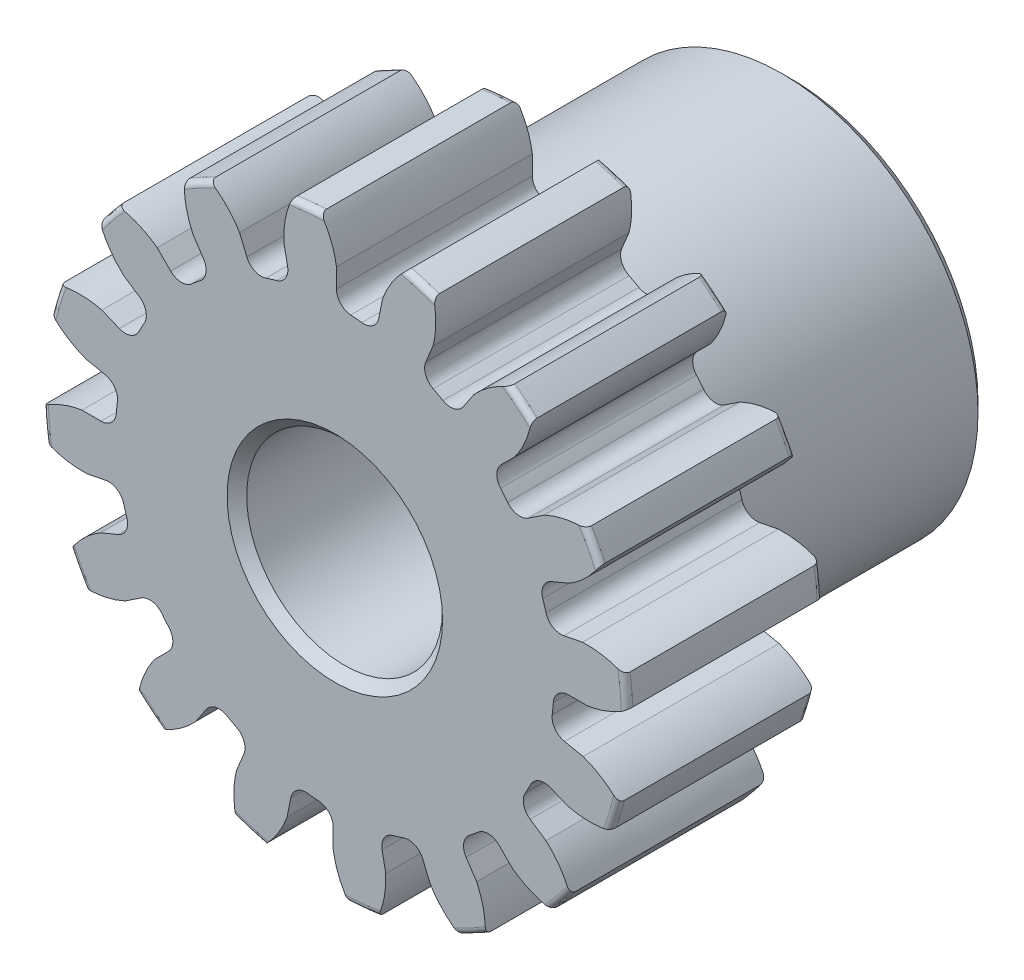
SolidWorks part; units mm, degrees
ref_plane "Front" through (0, 0, 0) normal (0, 0, 1) x (1, 0, 0)
ref_plane "Top" through (0, 0, 0) normal (0, 1, 0) x (1, 0, 0)
ref_plane "Right" through (0, 0, 0) normal (1, 0, 0) x (0, 0, -1)
sketch "Sketch1" plane through (0, 0, 0) normal (0, 0, 1) x (1, 0, 0)
  line L0 (-203.2, 0) -> (203.2, 0) construction
  circle A0 centre (0, 0) radius 7.112
  circle A1 centre (0, 0) radius 6.35 construction
  circle A3 centre (0, 0) radius 5.3261 construction
  dimension "D1" = 1.7859
  dimension "OD" = 14.224
  dimension "Ptich Dia" = 12.7
  dimension "Root Dia" = 10.6521
  dimension "D3" = 0.762
  dimension "Number of Teeth" = 406.4
extrude "Boss-Extrude1" add sketch "Sketch1" against normal blind 4.7625
sketch "Sketch2" plane through (0, 0, 0) normal (1, 0, 0) x (0, 0, -1)
  line L0 (4.7625, 0) -> (11.1125, 0)
  line L1 (4.7625, 0) -> (4.7625, 4.7625)
  line L2 (4.7625, 4.7625) -> (11.1125, 4.7625)
  line L3 (11.1125, 4.7625) -> (11.1125, 0)
  point P5 (11.1125, -4.7625)
  point P6 (0, -7.112)
  point P7 (4.7625, -7.112)
  point P9 (0, 7.112)
  dimension "Face Wd" = 4.7625
  dimension "B Hub Dia" = 9.525
  dimension "D O'all Lg." = 11.1125
revolve "Revolve1" add sketch "Sketch2" angle 360 mid plane about L0
fillet "Fillet2" radius 0.1422 3 edges at (7.112, 0, -4.7625) (7.112, 0, 0) (4.7625, 0, -4.7625)
sketch "Sketch3" plane through (0, 0, 0) normal (0, 0, 1) x (1, 0, 0)
  line L0 (0, 0) -> (0, 7.112) construction
  line L1 (-1.5393, 5.9519) -> (0, 6.35)
  line L2 (-9.5921, 6.35) -> (9.5921, 6.35) construction
  line L3 (-9.2865, 3.9483) -> (9.2865, 8.7517) construction
  line L4 (-1.5393, 5.9519) -> (0, 0) construction
  line L5 (-3.9262, 4.7307) -> (0, 0) construction
  line L6 (-3.9262, 4.7307) -> (-0.6424, 7.456) construction
  line L7 (-1.0733, 6.0533) -> (0, 0) construction
  line L8 (-1.0733, 6.0533) -> (0.0225, 6.2476) construction
  arc A0 (-1.5393, 5.9519) -> (-3.9262, 4.7307) centre (0, 0) ccw
  circle A1 centre (0, 0) radius 6.35 construction
  circle A2 centre (0, 0) radius 6.1477 construction
  arc A3 (-1.5393, 5.9519) -> (-1.0733, 6.0533) centre (0, 0) cw
  circle A4 centre (0, 0) radius 7.112 construction
  point P6 (0, 6.35)
  dimension "D1" = 1.5899
  dimension "Pressure Angle" = 14.5
  dimension "D2" = 2.7029
  dimension "D3" = 4.2674
  dimension "D4" = 0.477
  dimension "D5" = 1.1129
sketch "Sketch4" plane through (0, 0, 0) normal (0, 0, 1) x (1, 0, 0)
  line L0 (0, 0) -> (0.6194, 6.289) construction
  line L1 (0.0398, 6.1476) -> (0.0398, 5.3259)
  line L2 (0, 6.35) -> (1.2388, 6.228) construction
  line L3 (1.1603, 6.0372) -> (1, 5.2313)
  line L4 (0.0398, 5.3259) -> (0, 0) construction
  line L5 (0, 0) -> (0, 7.112) construction
  line L6 (-3.9262, 4.7307) -> (-0.6424, 7.456) construction
  line L7 (-3.9262, 4.7307) -> (-0.6424, 7.456) construction
  arc A0 (1, 5.2313) -> (0.0398, 5.3259) centre (0, 0) ccw
  arc A1 (0, 6.35) -> (1.2388, 6.228) centre (0, 0) cw construction
  circle A2 centre (0, 0) radius 6.35 construction
  circle A3 centre (0, 0) radius 6.1477 construction
  circle A4 centre (0, 0) radius 5.3261 construction
  arc A5 (2.0846, 7.1874) -> (-0.6424, 7.456) centre (0, 0) ccw
  spline S0 degree 2 poles (-0.6424, 7.456) (-0.0701, 6.8828) (0.0398, 6.1476) knots 0 0 0 1 1 1
  spline S1 degree 2 poles (2.0846, 7.1874) (1.4115, 6.7368) (1.1603, 6.0372) knots 0 0 0 1 1 1
  dimension "D1" = 1.2468
extrude "Cut-Extrude1" cut sketch "Sketch4" against normal through all
fillet "Fillet1" radius 0.374 2 edges at (1, 5.2313, -2.3813) (0.0398, 5.3259, -2.3813)
pattern_circular "CirPattern1" count 16 over 360 about axis through (0, 0, -4.7625) along (0, 0, 1) of "Cut-Extrude1", "Fillet1"
sketch "Sketch5" plane through (0, 0, 0) normal (0, 0, 1) x (1, 0, 0)
  circle A0 centre (0, 0) radius 2.3813
  circle A1 centre (0, 0) radius 1.5875 construction
  dimension "Bore Min" = 4.7625
  dimension "Bore Max" = 3.175
extrude "Cut-Extrude2" cut sketch "Sketch5" against normal through all
chamfer "Chamfer1" distance 0.2381 angle 45 3 edges at (4.7625, 0, -11.1125) (2.3813, 0, 0) (2.3813, 0, -11.1125)
sketch "Pitch Dia" plane through (0, 0, 0) normal (0, 0, 1) x (1, 0, 0)
  circle A0 centre (0, 0) radius 6.35 construction
  circle A1 centre (0, 0) radius 6.35 construction
equation "\"D1@Boss-Extrude1\" = \"Face Wd@Sketch2\""
equation "\"D2@Sketch3\" = \"D1@Sketch3\"*1.7"
equation "\"D3@Sketch3\" = \"D1@Sketch3\"+\"D2@Sketch3\"-.001"
equation "\"D4@Sketch3\" = \"D1@Sketch3\"*.3"
equation "\"D5@Sketch3\" = \"D1@Sketch3\"-\"D4@Sketch3\""
equation "\"D1@Sketch4\" = 1.5708/(\"Number of Teeth@Sketch1\"/\"Ptich Dia@Sketch1\")"
equation "\"D1@Chamfer1\" = \"B Hub Dia@Sketch2\"*.025"
equation "\"D1@CirPattern1\" = \"Number of Teeth@Sketch1\""
equation "\"D1@Fillet1\" = \"D1@Sketch4\"*.3"
equation "\"D1@Fillet2\" = \"OD@Sketch1\"*.01"
equation "\"D1@Sketch1\" = 2.250/(\"Number of Teeth@Sketch1\"/\"Ptich Dia@Sketch1\")"
